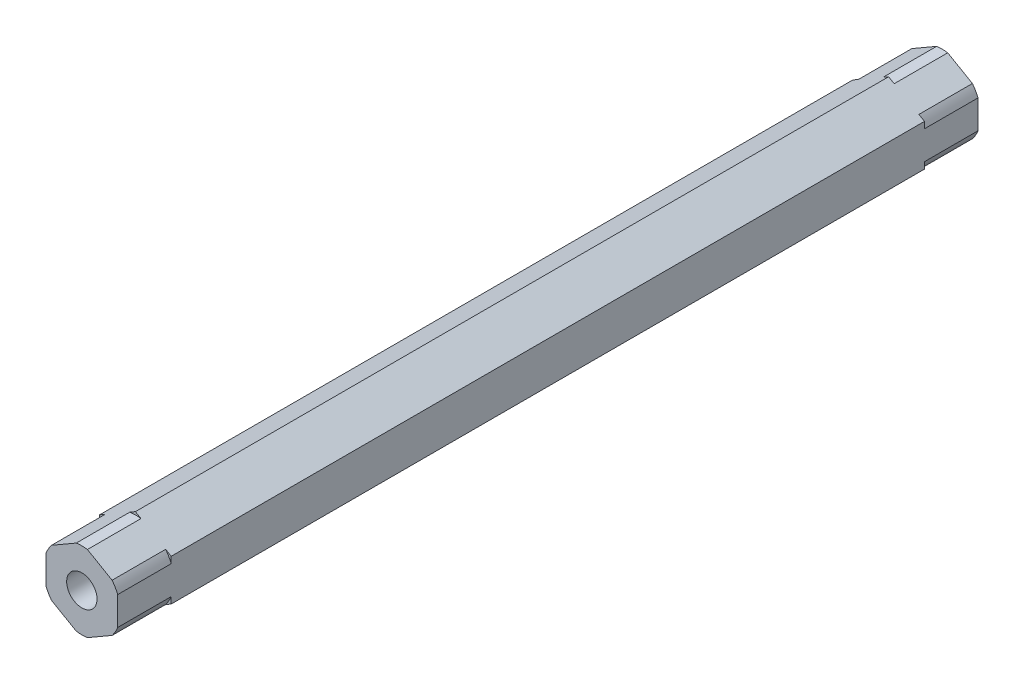
SolidWorks part; units mm, degrees
material "7075-T6 (SN)"
ref_plane "Front Plane" through (0, 0, 0) normal (0, 0, 1) x (1, 0, 0)
ref_plane "Top Plane" through (0, 0, 0) normal (0, 1, 0) x (1, 0, 0)
ref_plane "Right Plane" through (0, 0, 0) normal (1, 0, 0) x (0, 0, -1)
sketch "Sketch1" plane through (0, 0, 0) normal (0, 0, 1) x (1, 0, 0)
  line L1 (4.7625, 2.7496) -> (0, 5.4993)
  line L2 (0, 5.4993) -> (-4.7625, 2.7496)
  line L3 (-4.7625, 2.7496) -> (-4.7625, -2.7496)
  line L4 (-4.7625, -2.7496) -> (0, -5.4993)
  line L5 (0, -5.4993) -> (4.7625, -2.7496)
  line L6 (4.7625, -2.7496) -> (4.7625, 2.7496)
  circle A0 centre (0, 0) radius 4.7625 construction
  point P1 (0, 0)
  dimension "D2" = 9.525
extrude "Boss-Extrude1" add sketch "Sketch1" along normal mid plane 114.3
sketch "Sketch2" plane through (0, 0, -57.15) normal (0, 0, -1) x (-1, 0, 0)
  circle A0 centre (0, 0) radius 2.0193
  dimension "D1" = 4.0386
extrude "Cut-Extrude1" cut sketch "Sketch2" against normal blind 19.05
mirror "Mirror1" about plane through (0, 0, 0) normal (0, 0, 1) of "Cut-Extrude1"
sketch "Sketch4" plane through (0, 0, 57.15) normal (0, 0, 1) x (1, 0, 0)
  circle A0 centre (0, 0) radius 5.125
  circle A1 centre (0, 0) radius 7.0574
  dimension "D1" = 10.25
extrude "Cut-Extrude2" cut sketch "Sketch4" against normal blind 7.112
mirror "Mirror2" about plane through (0, 0, 0) normal (0, 0, 1) of "Cut-Extrude2"
